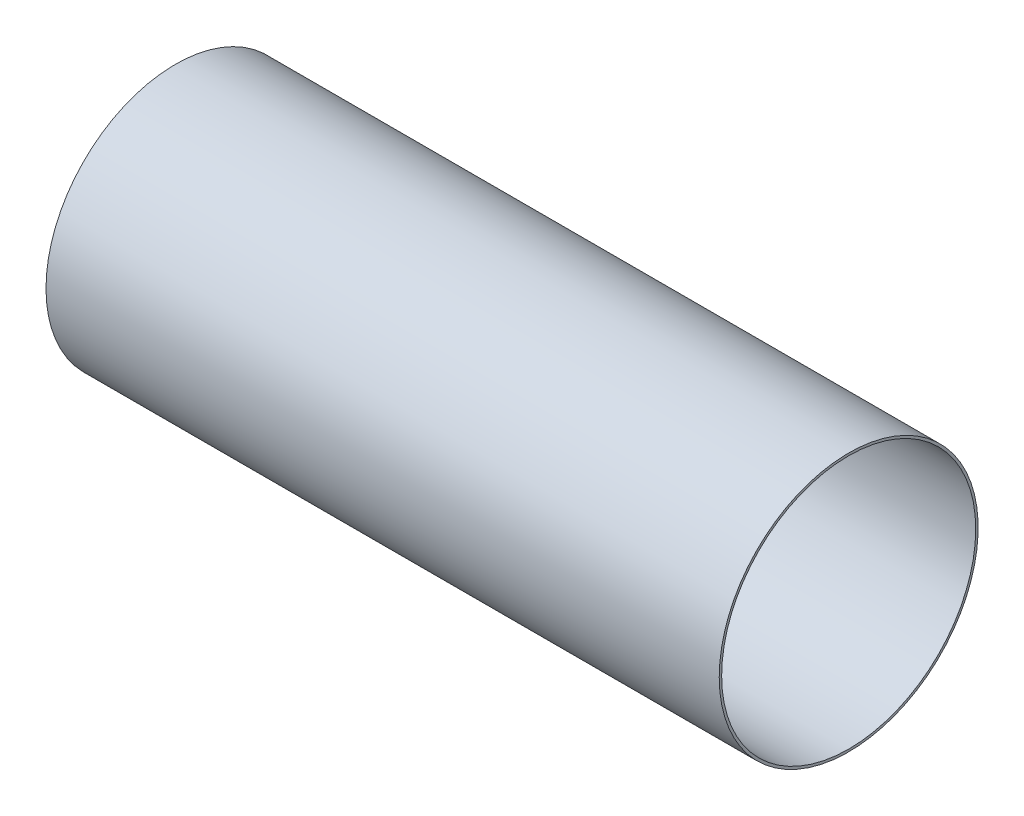
SolidWorks part; units mm, degrees
material "丙烯酸(中高冲击)"
ref_plane "前视基准面" through (0, 0, 0) normal (0, 0, 1) x (1, 0, 0)
ref_plane "上视基准面" through (0, 0, 0) normal (0, 1, 0) x (1, 0, 0)
ref_plane "右视基准面" through (0, 0, 0) normal (1, 0, 0) x (0, 0, -1)
sketch "草图2" plane through (0, 0, 0) normal (1, 0, 0) x (0, 0, -1)
  circle A0 centre (0, 0) radius 160
  circle A1 centre (0, 0) radius 157
extrude "凸台-拉伸1" add sketch "草图2" along normal blind 832
